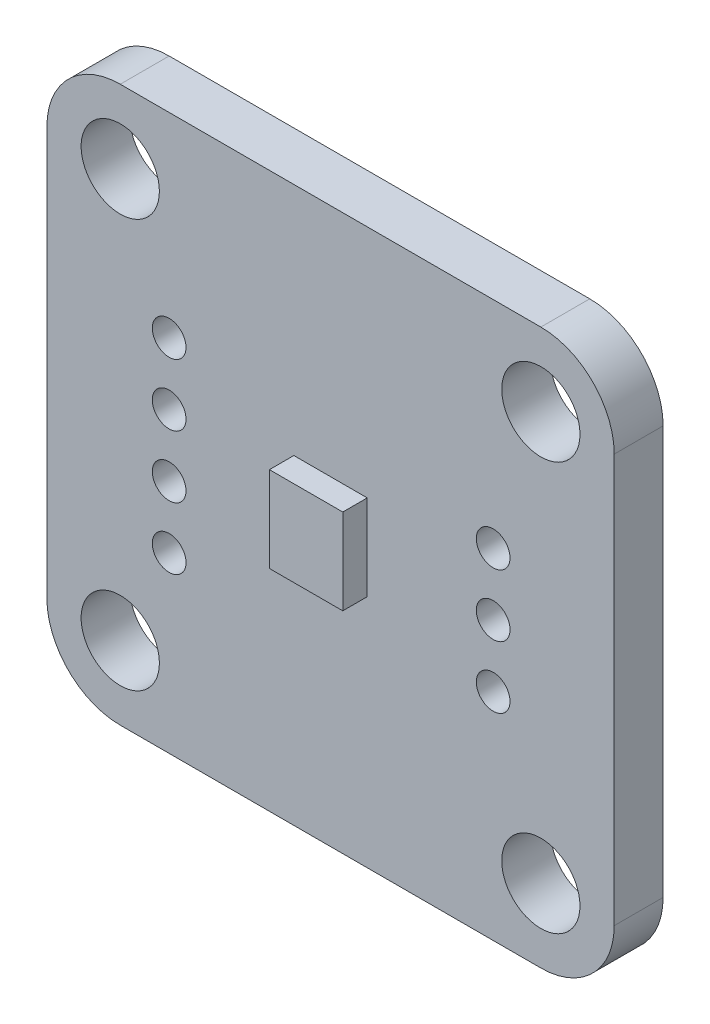
SolidWorks part; units mm, degrees
ref_plane "Plano frontal" through (0, 0, 0) normal (0, 0, 1) x (1, 0, 0)
ref_plane "Plano superior" through (0, 0, 0) normal (0, 1, 0) x (1, 0, 0)
ref_plane "Plano direito" through (0, 0, 0) normal (1, 0, 0) x (0, 0, -1)
sketch "Esboço2" plane through (0, 0, 0) normal (0, 0, 1) x (1, 0, 0)
  line L1 (8.6, -11.35) -> (-8.6, -11.35)
  line L2 (11.6, -8.35) -> (11.6, 8.35)
  line L3 (8.6, 11.35) -> (-8.6, 11.35)
  line L4 (-11.6, -8.35) -> (-11.6, 8.35)
  line L5 (11.6, -11.35) -> (-11.6, 11.35) construction
  line L6 (11.6, 11.35) -> (-11.6, -11.35) construction
  arc A0 (-8.6, 11.35) -> (-11.6, 8.35) centre (-8.6, 8.35) ccw
  arc A1 (-8.6, -11.35) -> (-11.6, -8.35) centre (-8.6, -8.35) cw
  arc A2 (8.6, -11.35) -> (11.6, -8.35) centre (8.6, -8.35) ccw
  arc A3 (11.6, 8.35) -> (8.6, 11.35) centre (8.6, 8.35) ccw
  circle A4 centre (-8.6, -8.35) radius 1.6
  circle A5 centre (-8.6, 8.35) radius 1.6
  circle A6 centre (8.6, 8.35) radius 1.6
  circle A7 centre (8.6, -8.35) radius 1.6
  point P0 (0, 0)
  dimension "D3" = 3
  dimension "D4" = 3
  dimension "D5" = 3.2
  dimension "D1" = 22.7
  dimension "D2" = 23.2
extrude "Ressalto-extrusão1" add sketch "Esboço2" along normal blind 2
sketch "Esboço3" plane through (0, 0, 2) normal (0, 0, 1) x (1, 0, 0)
  line L0 (-8.6, -11.35) -> (8.6, -11.35) construction
  line L1 (-11.6, 8.35) -> (-11.6, -8.35) construction
  line L2 (11.6, -8.35) -> (11.6, 8.35) construction
  circle A0 centre (-6.6, -4.25) radius 0.69
  circle A1 centre (-6.6, -1.71) radius 0.69
  circle A2 centre (-6.6, 0.83) radius 0.69
  circle A3 centre (-6.6, 3.37) radius 0.69
  circle A4 centre (6.65, 0) radius 0.69
  circle A5 centre (6.65, 2.54) radius 0.69
  circle A6 centre (6.65, -2.54) radius 0.69
  dimension "D1" = 1.38
  dimension "D2" = 7.1
  dimension "D3" = 5
  dimension "D5" = 4.95
  dimension "D4" = 4
  dimension "D6" = 2
  dimension "D7" = 2
extrude "Corte-extrusão1" cut sketch "Esboço3" against normal blind 2
sketch "Esboço4" plane through (0, 0, 2) normal (0, 0, 1) x (1, 0, 0)
  line L1 (-1.5, -1.75) -> (1.5, -1.75)
  line L2 (-1.5, -1.75) -> (-1.5, 1.75)
  line L3 (-1.5, 1.75) -> (1.5, 1.75)
  line L4 (1.5, -1.75) -> (1.5, 1.75)
  line L5 (-1.5, -1.75) -> (1.5, 1.75) construction
  line L6 (-1.5, 1.75) -> (1.5, -1.75) construction
  point P0 (0, 0)
  dimension "D1" = 3.5
  dimension "D2" = 3
extrude "Ressalto-extrusão2" add sketch "Esboço4" along normal blind 1
